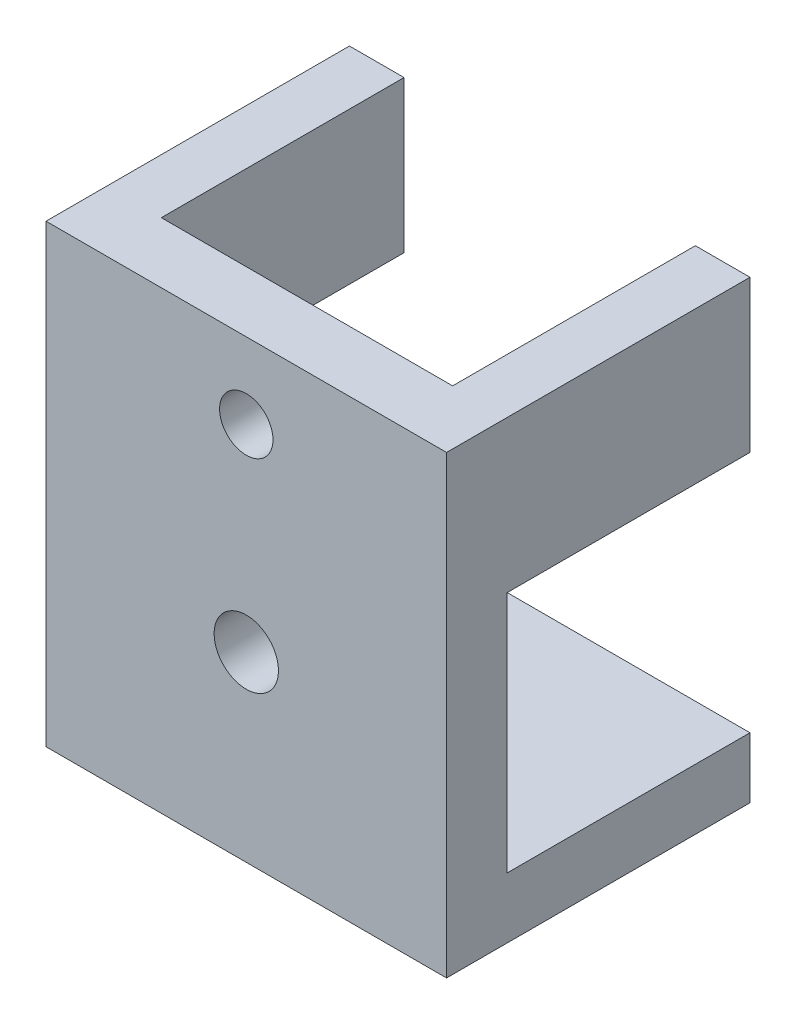
SolidWorks part; units mm, degrees
ref_plane "Front Plane" through (0, 0, 0) normal (0, 0, 1) x (1, 0, 0)
ref_plane "Top Plane" through (0, 0, 0) normal (0, 1, 0) x (1, 0, 0)
ref_plane "Right Plane" through (0, 0, 0) normal (1, 0, 0) x (0, 0, -1)
sketch "Sketch2" plane through (0, 0, 0) normal (0, 0, 1) x (1, 0, 0)
  line L1 (0, 0) -> (33, 0)
  line L2 (0, 0) -> (0, 37.5)
  line L3 (0, 37.5) -> (33, 37.5)
  line L4 (33, 0) -> (33, 37.5)
  dimension "D1" = 37.5
  dimension "D2" = 33
extrude "Boss-Extrude1" add sketch "Sketch2" along normal blind 5
sketch "Sketch3" plane through (0, 0, 0) normal (0, 0, 1) x (1, 0, 0)
  line L0 (33, 0) -> (33, 37.5) construction
  line L1 (0, 0) -> (33, 0)
  line L2 (0, 0) -> (0, 5)
  line L3 (0, 5) -> (33, 5)
  line L4 (33, 0) -> (33, 5)
  dimension "D1" = 5
extrude "Boss-Extrude2" add sketch "Sketch3" against normal blind 20
sketch "Sketch6" plane through (0, 0, 0) normal (0, -1, 0) x (1, 0, 0)
  line L0 (0, -20) -> (33, -20) construction
  line L2 (16.5, 5) -> (16.5, -20) construction
  line L3 (0, 5) -> (33, 5) construction
  line L4 (0, -20) -> (33, -20) construction
  circle A0 centre (16.5, -10) radius 2.65
  dimension "D1" = 5.3
  dimension "D2" = 10
extrude "Cut-Extrude2" cut sketch "Sketch6" against normal blind 10
sketch "Sketch7" plane through (0, 0, 0) normal (0, 0, -1) x (-1, 0, 0)
  line L0 (0, 0) -> (-33, 0) construction
  line L2 (-16.5, 37.5) -> (-16.5, 0) construction
  line L3 (-33, 37.5) -> (0, 37.5) construction
  line L4 (0, 0) -> (-33, 0) construction
  circle A0 centre (-16.5, 15) radius 2.65
  dimension "D1" = 5.3
  dimension "D2" = 15
extrude "Cut-Extrude3" cut sketch "Sketch7" against normal blind 10
sketch "Sketch8" plane through (0, 0, 0) normal (0, 0, -1) x (-1, 0, 0)
  line L1 (-33, 37.5) -> (-28.5, 37.5)
  line L2 (-33, 37.5) -> (-33, 25)
  line L3 (-33, 25) -> (-28.5, 25)
  line L4 (-28.5, 37.5) -> (-28.5, 25)
  line L5 (0, 37.5) -> (-4.5, 37.5)
  line L6 (0, 37.5) -> (0, 25)
  line L7 (0, 25) -> (-4.5, 25)
  line L8 (-4.5, 37.5) -> (-4.5, 25)
  dimension "D1" = 4.5
  dimension "D2" = 4.5
  dimension "D3" = 12.5
  dimension "D4" = 12.5
extrude "Boss-Extrude3" add sketch "Sketch8" along normal blind 20
sketch "Sketch9" plane through (0, 0, 5) normal (0, 0, 1) x (1, 0, 0)
  line L0 (33, 37.5) -> (0, 37.5) construction
  line L2 (16.5, 37.5) -> (16.5, 0) construction
  line L3 (0, 0) -> (33, 0) construction
  circle A0 centre (16.5, 31.25) radius 2.2
  dimension "D1" = 4.4
  dimension "D2" = 6.25
extrude "Cut-Extrude4" cut sketch "Sketch9" against normal blind 10
